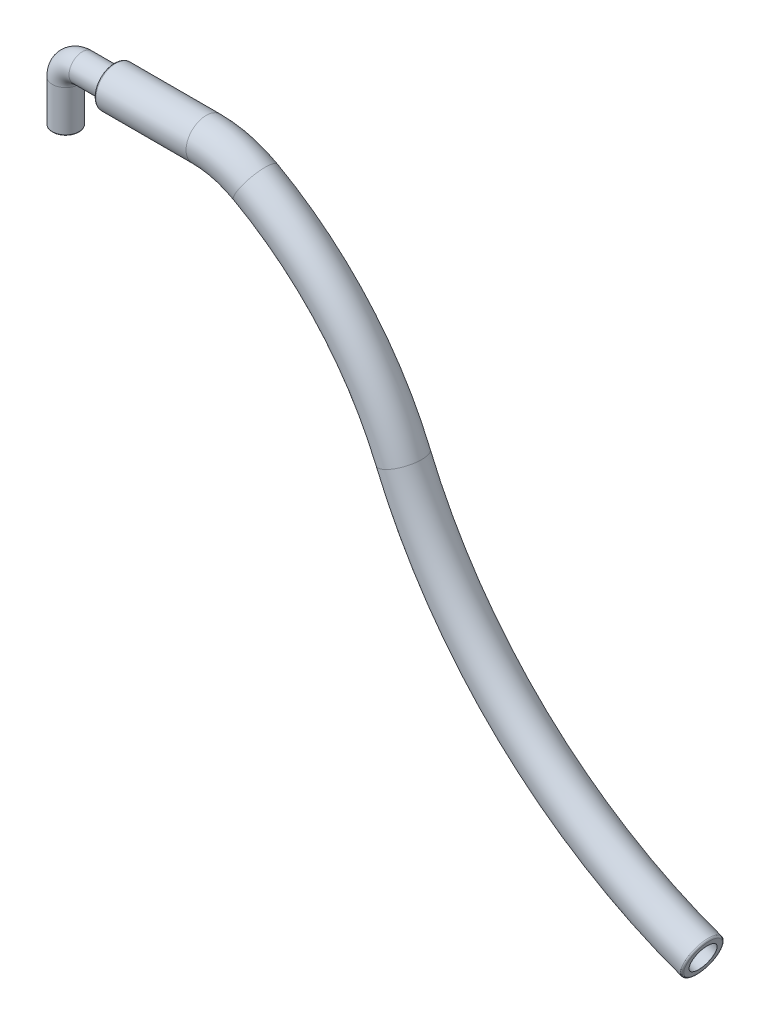
SolidWorks part; units mm, degrees
ref_plane "Alzado" through (0, 0, 0) normal (0, 0, 1) x (1, 0, 0)
ref_plane "Planta" through (0, 0, 0) normal (0, 1, 0) x (1, 0, 0)
ref_plane "Vista lateral" through (0, 0, 0) normal (1, 0, 0) x (0, 0, -1)
sketch "Croquis1" plane through (0, 0, 0) normal (0, 0, 1) x (1, 0, 0)
  line L0 (0, -10) -> (0, -35)
  line L1 (10, 0) -> (50, 0)
  line L2 (0, -10) -> (23.5725, -10) construction
  line L3 (50, 0) -> (50, 2.9617) construction
  line L4 (50, 0) -> (53.7086, 0) construction
  line L5 (16, 0) -> (16, 26.592) construction
  line L6 (0, -31) -> (18.2487, -31) construction
  line L7 (46, 0) -> (46, 28.3563) construction
  line L8 (0, -11) -> (26.2947, -11) construction
  arc A0 (0, -10) -> (10, 0) centre (10, -10) cw
  point P6 (0, 0)
  dimension "D1" = 10
  dimension "D2" = 25
  dimension "D3" = 40
  dimension "D4" = 4
  dimension "D5" = 30
  dimension "D6" = 4
  dimension "D7" = 20
ref_plane "Plano1" through (0, -35, 0) normal (0, -1, 0) x (1, 0, 0)
sketch "Croquis2" plane through (0, -35, 0) normal (0, -1, 0) x (1, 0, 0)
  line L0 (0, 0) -> (0, -10.1083) construction
  line L1 (0, 0) -> (-12.2077, 0) construction
  circle A0 centre (0, 0) radius 8
  dimension "D1" = 16
sweep "Barrer1" add profiles "Croquis2" path "Croquis1"
shell "Vaciado2" thickness 2
fillet "Redondeo1" radius 0.5 4 edges at (6, -35, 0) (8, -35, 0) (50, -8, 0) (50, -6, 0)
sketch "Croquis3" plane through (0, -35, 0) normal (0, -1, 0) x (1, 0, 0)
  line L0 (0, 0) -> (10.9751, 0) construction
  line L1 (0, 0) -> (0, -13.0055) construction
sketch "Croquis5" plane through (50, 0, 0) normal (1, 0, 0) x (0, 0, -1)
  line L0 (0, 0) -> (12.3974, 0) construction
sketch "Croquis6" plane through (0, 0, 0) normal (0, 0, 1) x (1, 0, 0)
  line L0 (29.0946, 0) -> (84.2006, 0)
  arc A0 (84.2006, 0) -> (113.8084, -7.6886) centre (84.2006, -60.852) cw
  arc A1 (113.8084, -7.6886) -> (202.4559, -106.7229) centre (14.7578, -185.5429) cw
  arc A2 (202.4559, -106.7229) -> (382.2584, -276.412) centre (484.0134, 11.5115) ccw
ref_plane "Plano2" through (29.0946, 0, 0) normal (1, 0, 0) x (0, 0, -1)
sketch "Croquis7" plane through (29.0946, 0, 0) normal (1, 0, 0) x (0, 0, -1)
  circle A0 centre (0, 0) radius 12
  dimension "D1" = 24
sweep "Barrer2" add profiles "Croquis7" path "Croquis6"
shell "Vaciado3" thickness 4
fillet "Redondeo2" radius 1 2 edges at (382.2584, -276.412, -12) (29.0946, 0, -12)
